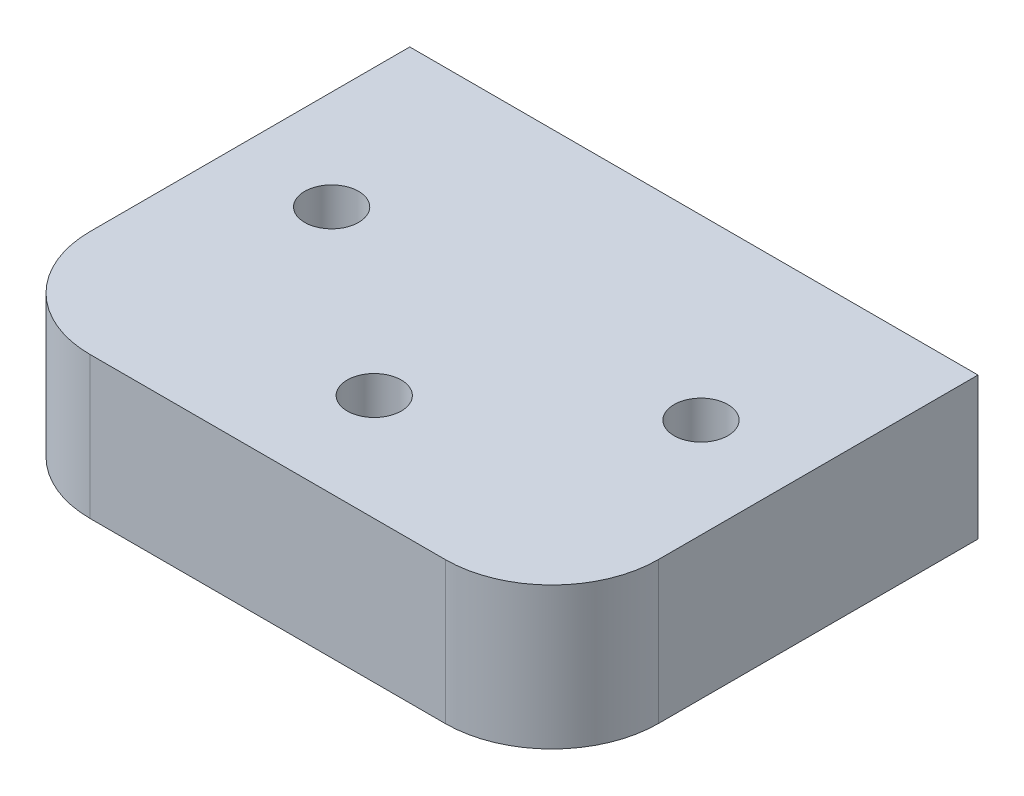
SolidWorks part; units mm, degrees
ref_plane "Front Plane" through (0, 0, 0) normal (0, 0, 1) x (1, 0, 0)
ref_plane "Top Plane" through (0, 0, 0) normal (0, 1, 0) x (1, 0, 0)
ref_plane "Right Plane" through (0, 0, 0) normal (1, 0, 0) x (0, 0, -1)
sketch "Sketch1" plane through (0, 0, 0) normal (0, 1, 0) x (1, 0, 0)
  line L1 (0, 0) -> (40, 0)
  line L2 (0, 0) -> (0, -22.5)
  line L3 (7.5, -30) -> (32.5, -30)
  line L4 (40, 0) -> (40, -22.5)
  arc A0 (32.5, -30) -> (40, -22.5) centre (32.5, -22.5) ccw
  arc A1 (0, -22.5) -> (7.5, -30) centre (7.5, -22.5) ccw
  point P9 (0, -30)
  dimension "D3" = 7.5
  dimension "D1" = 40
  dimension "D2" = 30
extrude "Boss-Extrude1" add sketch "Sketch1" along normal blind 10
hole_wizard "#6 Clearance Hole1" positions "Sketch2" profile "Sketch3" hole size "#6" standard "ANSI Inch" end condition through all
sketch "Sketch2" plane through (0, 10, 0) normal (0, 1, 0) x (1, 0, 0)
  line L0 (7.5, -30) -> (32.5, -30) construction
  point P0 (7, -12.5)
  point P2 (33, -12.5)
  point P4 (20, -22.5)
  point P7 (0, 0)
  point P10 (20, -30)
  point P12 (0, 0)
  point P15 (0, 0)
  point P18 (0, 0)
  point P19 (20, -20.06)
  point P20 (0, 0)
  dimension "D1" = 10
  dimension "D2" = 26
  dimension "D3" = 13
sketch "Sketch3" plane through (7, 10, 12.5) normal (1, 0, 0) x (0, 0, 1)
  line L0 (0, 0) -> (0, 10)
  line L1 (0, 10) -> (1.8986, 10)
  line L2 (1.8986, 10) -> (1.8986, 0)
  line L5 (1.8986, 0) -> (0, 0)
  line L11 (0, -6.35) -> (0, 107.95) construction
  dimension "Thru Hole Dia." = 3.7973
  dimension "Thru Hole Depth" = 10
hole_wizard "#6-32 Tapped Hole1" positions "Sketch4" profile "Sketch6" tap size "#6-32" standard "ANSI Inch"
sketch "Sketch4" plane through (0, 0, 0) normal (0, 0, -1) x (-1, 0, 0)
  line L1 (-40, 10) -> (-40, 0) construction
  line L2 (-40, 0) -> (0, 0) construction
  point P0 (-32.5, 5)
  point P2 (-20, 5)
  point P4 (-7.5, 5)
  point P7 (0, 0)
  point P12 (-40, 5)
  point P13 (0, 0)
  point P16 (-20, 0)
  dimension "D1" = 12.5
  dimension "D2" = 12.5
sketch "Sketch6" plane through (32.5, 5, 0) normal (1, 0, 0) x (0, 1, 0)
  line L0 (0, 0) -> (0, 10.3427)
  line L1 (0, 10.3427) -> (1.3525, 9.53)
  line L2 (1.3525, 9.53) -> (1.3525, 0)
  line L5 (1.3525, 0) -> (0, 0)
  line L10 (0, 10.3427) -> (-1.3526, 9.53) construction
  line L11 (0, -6.35) -> (0, 107.95) construction
  dimension "Tap Drill Dia." = 2.7051
  dimension "Tap Drill Depth" = 9.53
  dimension "Drill Angle" = 118
